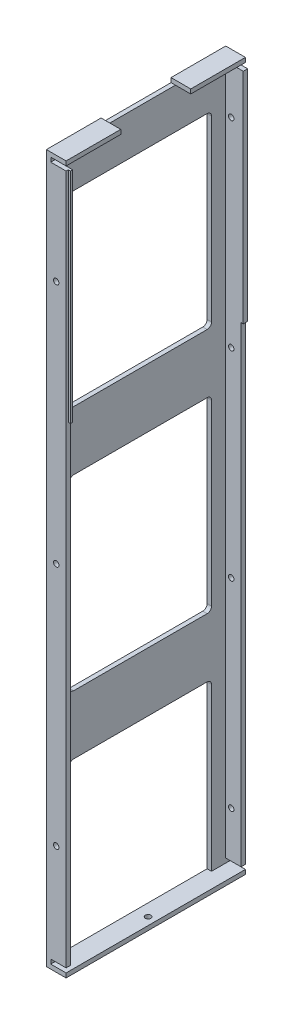
SolidWorks part; units mm, degrees
material "6061 Alloy"
ref_plane "Front Plane" through (0, 0, 0) normal (0, 0, 1) x (1, 0, 0)
ref_plane "Top Plane" through (0, 0, 0) normal (0, 1, 0) x (1, 0, 0)
ref_plane "Right Plane" through (0, 0, 0) normal (1, 0, 0) x (0, 0, -1)
sketch "Sketch1" plane through (0, 0, 0) normal (1, 0, 0) x (0, 0, -1)
  line L1 (-41, -161.75) -> (41, -161.75)
  line L2 (-41, -161.75) -> (-41, 161.75)
  line L3 (-41, 161.75) -> (41, 161.75)
  line L4 (41, -161.75) -> (41, 161.75)
  line L5 (-41, -161.75) -> (41, 161.75) construction
  line L6 (-41, 161.75) -> (41, -161.75) construction
  point P0 (0, 0)
  dimension "D1" = 323.5
  dimension "D2" = 82
extrude "Base Extrusion" add sketch "Sketch1" along normal blind 2
sketch "Sketch8" plane through (2, 0, 0) normal (1, 0, 0) x (0, 0, -1)
  line L1 (-30.5, 55.75) -> (30.5, 55.75)
  line L2 (-32.5, 57.75) -> (-32.5, 139.25)
  line L3 (-30.5, 141.25) -> (30.5, 141.25)
  line L4 (32.5, 57.75) -> (32.5, 139.25)
  line L5 (-32.5, 55.75) -> (32.5, 141.25) construction
  line L6 (-32.5, 141.25) -> (32.5, 55.75) construction
  line L7 (-30.5, -56.75) -> (30.5, -56.75)
  line L8 (-32.5, -54.75) -> (-32.5, 26.75)
  line L9 (-30.5, 28.75) -> (30.5, 28.75)
  line L10 (32.5, -54.75) -> (32.5, 26.75)
  line L11 (-32.5, -56.75) -> (32.5, 28.75) construction
  line L12 (-32.5, 28.75) -> (32.5, -56.75) construction
  line L13 (-32.5, -159.75) -> (32.5, -159.75)
  line L14 (-32.5, -159.75) -> (-32.5, -85.75)
  line L15 (-30.5, -83.75) -> (30.5, -83.75)
  line L16 (32.5, -159.75) -> (32.5, -85.75)
  line L17 (-32.5, -159.75) -> (32.5, -83.75) construction
  line L18 (-32.5, -83.75) -> (32.5, -159.75) construction
  line L19 (-41, -161.75) -> (41, -161.75) construction
  arc A0 (-30.5, 55.75) -> (-32.5, 57.75) centre (-30.5, 57.75) cw
  arc A1 (-32.5, 26.75) -> (-30.5, 28.75) centre (-30.5, 26.75) cw
  arc A2 (-30.5, -56.75) -> (-32.5, -54.75) centre (-30.5, -54.75) cw
  arc A3 (-32.5, -85.75) -> (-30.5, -83.75) centre (-30.5, -85.75) cw
  arc A4 (30.5, -83.75) -> (32.5, -85.75) centre (30.5, -85.75) cw
  arc A5 (30.5, -56.75) -> (32.5, -54.75) centre (30.5, -54.75) ccw
  arc A6 (30.5, 28.75) -> (32.5, 26.75) centre (30.5, 26.75) cw
  arc A7 (30.5, 55.75) -> (32.5, 57.75) centre (30.5, 57.75) ccw
  arc A8 (30.5, 141.25) -> (32.5, 139.25) centre (30.5, 139.25) cw
  arc A9 (-32.5, 139.25) -> (-30.5, 141.25) centre (-30.5, 139.25) cw
  point P0 (0, 98.5)
  point P5 (0, -14)
  point P10 (0, -121.75)
  point P45 (0, 141.25)
  point P46 (0, 28.75)
  point P47 (0, -83.75)
  dimension "D1" = 2
  dimension "D2" = 65
  dimension "D3" = 76
  dimension "D4" = 85.5
  dimension "D5" = 85.5
  dimension "D6" = 27
  dimension "D7" = 27
  dimension "D8" = 65
  dimension "D9" = 65
  dimension "D10" = 2
extrude "Access Ports" cut sketch "Sketch8" against normal through all
sketch "Sketch4" plane through (2, 0, 0) normal (1, 0, 0) x (0, 0, -1)
  line L1 (39, 159.75) -> (-39, 159.75)
  line L2 (-39, 159.75) -> (-39, -159.75)
  line L3 (-39, -159.75) -> (39, -159.75)
  line L4 (39, -159.75) -> (39, 159.75)
  line L5 (41, -161.75) -> (41, 161.75)
  line L6 (41, 161.75) -> (-41, 161.75)
  line L7 (-41, 161.75) -> (-41, -161.75)
  line L8 (-41, -161.75) -> (41, -161.75)
  line L9 (41, -161.75) -> (41, 161.75)
  line L10 (41, 161.75) -> (-41, 161.75)
  line L11 (-41, 161.75) -> (-41, -161.75)
  line L12 (-41, -161.75) -> (41, -161.75)
  dimension "D1" = 0
  dimension "D2" = 2
extrude "Corner Rail Mounts" add sketch "Sketch4" along normal blind 7
hole_wizard "M3x0.5 Tapped Hole For End" positions "Sketch12" profile "Sketch11" tap size "M3x0.5" standard "Ansi Metric"
sketch "Sketch12" plane through (0, -161.75, 0) normal (0, -1, 0) x (1, 0, 0)
  line L5 (0, 41) -> (0, -41) construction
  line L6 (9, 41) -> (9, -41) construction
  point P1 (5.5, 0)
  point P26 (0, 0)
  dimension "D1" = 3.5
sketch "Sketch11" plane through (5.5, -161.75, 0) normal (1, 0, 0) x (0, 0, -1)
  line L0 (0, 0) -> (0, 2)
  line L1 (0, 2) -> (1.25, 2)
  line L2 (1.25, 2) -> (1.25, 0)
  line L5 (1.25, 0) -> (0, 0)
  line L11 (0, -6.35) -> (0, 107.95) construction
  dimension "Thru Tap Drill Dia." = 2.5
  dimension "Thru Tap Drill Depth" = 2
cosmetic thread "Hole Thread15" parameters "D1"=2, "D2"=3
sketch "Sketch14" plane through (0, 161.75, 0) normal (0, 1, 0) x (1, 0, 0)
  line L0 (9, 41) -> (9, -41) construction
  line L3 (9, -16) -> (0, -16)
  line L4 (0, 41) -> (0, -41) construction
  line L5 (0, -16) -> (0, 16)
  line L6 (0, 16) -> (9, 16)
  line L9 (9, 16) -> (9, -16)
  point P9 (0, 0)
  dimension "D3" = 32
extrude "Antenna Cutout" cut sketch "Sketch14" against normal blind 2
sketch "Sketch15" plane through (9, 0, 0) normal (1, 0, 0) x (0, 0, -1)
  line L0 (-39, -159.75) -> (-41, -159.75)
  line L2 (-41, -159.75) -> (-41, -157.75)
  line L3 (-41, -157.75) -> (-39, -157.75)
  line L5 (-39, -157.75) -> (-39, -159.75)
  line L6 (39, -159.75) -> (41, -159.75)
  line L9 (41, -159.75) -> (41, -157.75)
  line L10 (41, -157.75) -> (39, -157.75)
  line L11 (39, -157.75) -> (39, -159.75)
  line L12 (39, 159.75) -> (41, 159.75)
  line L13 (41, 159.75) -> (41, 157.75)
  line L14 (41, 157.75) -> (39, 157.75)
  line L15 (39, 157.75) -> (39, 159.75)
  line L16 (-39, 159.75) -> (-41, 159.75)
  line L17 (-41, 159.75) -> (-41, 157.75)
  line L18 (-41, 157.75) -> (-39, 157.75)
  line L19 (-39, 157.75) -> (-39, 159.75)
  line L20 (-41, 161.75) -> (-41, -161.75) construction
  line L21 (-39, 159.75) -> (-39, -159.75) construction
  line L22 (39, -159.75) -> (39, 159.75) construction
  line L23 (41, -161.75) -> (41, 161.75) construction
  line L24 (39, 159.75) -> (16, 159.75) construction
  line L25 (-39, -159.75) -> (39, -159.75) construction
  dimension "D1" = 2
extrude "Slits In Corners" cut sketch "Sketch15" against normal up to surface (7 mm away) up to face at (2, -14, 0)
hole_wizard "M3x0.5 Tapped Holes For Rails" positions "3DSketch1" profile "Sketch16" tap size "M3x0.5" standard "Ansi Metric"
sketch3d "3DSketch1"
  line L1 (4.5, 161.75, -41) -> (4.5, 136.75, -41) construction
  line L2 (9, 161.75, -41) -> (0, 161.75, -41) construction
  line L3 (4.5, 136.75, -41) -> (4.5, 45.5833, -41) construction
  line L4 (4.5, 45.5833, -41) -> (4.5, -45.5833, -41) construction
  line L5 (4.5, -45.5833, -41) -> (4.5, -136.75, -41) construction
  line L6 (4.5, -136.75, -41) -> (4.5, -161.75, -41) construction
  line L9 (9, -161.75, -41) -> (0, -161.75, -41) construction
  line L10 (2, 157.75, -41) -> (9, 157.75, -41) construction
  line L11 (4.5, 161.75, 41) -> (4.5, 111.75, 41) construction
  line L13 (4.5, 111.75, 41) -> (4.5, 0, 41) construction
  line L14 (4.5, 0, 41) -> (4.5, -111.75, 41) construction
  line L18 (2, 157.75, 41) -> (9, 157.75, 41) construction
  line L20 (4.5, -111.75, 41) -> (4.5, -161.75, 41) construction
  line L21 (9, -161.75, 41) -> (0, -161.75, 41) construction
  line L23 (2, -157.75, 41) -> (9, -157.75, 41) construction
  line L24 (9, 161.75, 41) -> (0, 161.75, 41) construction
  point P0 (4.5, 136.75, -41)
  point P2 (4.5, 45.5833, -41)
  point P4 (4.5, -45.5833, -41)
  point P6 (4.5, -136.75, -41)
  point P8 (4.5, 111.75, 41)
  point P10 (4.5, 0, 41)
  point P12 (4.5, -111.75, 41)
  point P75 (4.5, -161.75, 41)
  point P80 (4.5, 161.75, 41)
  dimension "D1" = 25
  dimension "D2" = 50
sketch "Sketch16" plane through (4.5, 136.75, -41) normal (1, 0, 0) x (0, 1, 0)
  line L0 (0, 0) -> (0, 2)
  line L1 (0, 2) -> (1.25, 2)
  line L2 (1.25, 2) -> (1.25, 0)
  line L5 (1.25, 0) -> (0, 0)
  line L11 (0, -6.35) -> (0, 107.95) construction
  dimension "Thru Tap Drill Dia." = 2.5
  dimension "Thru Tap Drill Depth" = 2
cosmetic thread "Hole Thread17" parameters "D2"=3
cosmetic thread "Hole Thread18" parameters "D2"=3
cosmetic thread "Hole Thread19" parameters "D2"=3
cosmetic thread "Hole Thread20" parameters "D2"=3
cosmetic thread "Hole Thread21" parameters "D2"=3
cosmetic thread "Hole Thread22" parameters "D2"=3
cosmetic thread "Hole Thread23" parameters "D2"=3
sketch "Sketch17" plane through (9, 0, 0) normal (1, 0, 0) x (0, 0, -1)
  line L0 (41, 157.75) -> (41, 57.75)
  line L1 (41, -157.75) -> (41, 157.75) construction
  line L2 (41, 57.75) -> (39, 57.75)
  line L3 (39, -157.75) -> (39, 157.75) construction
  line L4 (39, 57.75) -> (39, 157.75)
  line L5 (39, 157.75) -> (41, 157.75)
  line L6 (-39, 157.75) -> (-39, 57.75)
  line L7 (-39, 157.75) -> (-39, -157.75) construction
  line L8 (-40, 57.75) -> (-40, 157.75)
  line L9 (-41, 157.75) -> (-39, 157.75) construction
  line L10 (-40, 157.75) -> (-39, 157.75)
  line L11 (-39, 57.75) -> (-40, 57.75)
  dimension "D1" = 100
extrude "Support For Payload" add sketch "Sketch17" along normal blind 1
